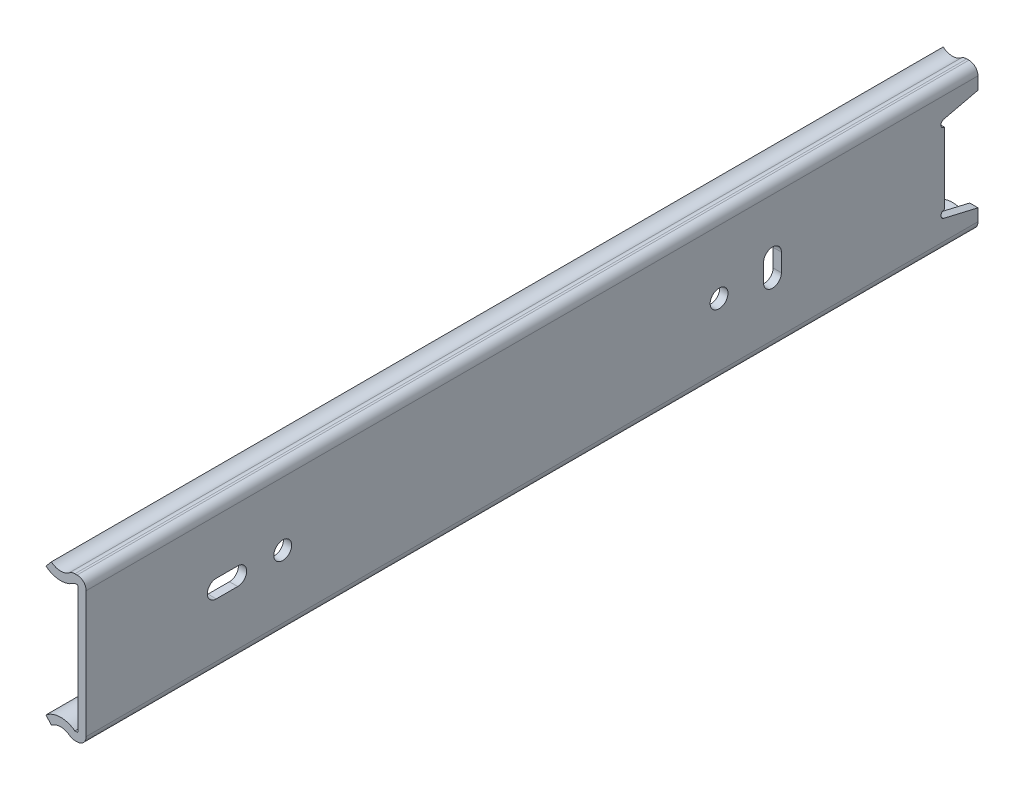
SolidWorks part; units mm, degrees
ref_plane "Front Plane" through (0, 0, 0) normal (0, 0, 1) x (1, 0, 0)
ref_plane "Top Plane" through (0, 0, 0) normal (0, 1, 0) x (1, 0, 0)
ref_plane "Right Plane" through (0, 0, 0) normal (1, 0, 0) x (0, 0, -1)
sketch "Sketch1" plane through (0, 0, 0) normal (0, 0, 1) x (1, 0, 0)
  line L0 (5.1643, -10.7505) -> (5.5418, -10.7505)
  line L1 (5.5372, 10.7505) -> (5.1643, 10.7505)
  line L2 (0.3041, 10.8422) -> (1.2082, 11.9072)
  line L3 (5.6642, 10.6235) -> (5.6642, -10.6235)
  line L4 (7.0612, -10.6235) -> (7.0612, 10.6235)
  line L5 (1.2082, -11.9072) -> (0.3041, -10.8422)
  line L22 (5.5372, 12.1475) -> (5.1643, 12.1475)
  arc A0 (5.1643, -10.7505) -> (0.3041, -10.8422) centre (2.7922, -13.8683) ccw
  arc A1 (1.2082, -11.9072) -> (4.2365, -11.8325) centre (2.7686, -13.7451) cw
  arc A2 (4.2365, -11.8325) -> (5.1643, -12.1475) centre (5.1643, -10.6235) ccw
  arc A3 (7.0612, -10.6235) -> (5.5372, -12.1475) centre (5.5372, -10.6235) cw
  arc A4 (7.0612, 10.6235) -> (5.5372, 12.1475) centre (5.5372, 10.6235) ccw
  arc A5 (5.5372, 10.7505) -> (5.6642, 10.6235) centre (5.5372, 10.6235) cw
  arc A6 (5.5418, -10.7505) -> (5.6642, -10.6235) centre (5.5371, -10.6234) ccw
  arc A7 (5.1643, 10.7505) -> (5.087, 10.7242) centre (5.1643, 10.6235) ccw
  arc A8 (5.087, 10.7242) -> (0.3041, 10.8422) centre (2.7686, 13.7451) cw
  arc A9 (1.2082, 11.9072) -> (4.2365, 11.8325) centre (2.7686, 13.7451) ccw
  arc A10 (4.2365, 11.8325) -> (5.1643, 12.1475) centre (5.1643, 10.6235) cw
  arc A11 (5.5372, -12.1475) -> (5.1643, -12.1475) centre (5.3508, -7.096) cw
extrude "Boss-Extrude1" add sketch "Sketch1" along normal blind 150 contours L3 A6 L0 A0 L5 A1 A2 A11 A3 L4 A4 L22 A10 A9 L2 A8 A7 L1 A5
sketch "Sketch2" plane through (7.0612, 0, 0) normal (1, 0, 0) x (0, 0, -1)
  line L0 (0.1195, 8.5561) -> (0.1195, -8.6225)
  line L1 (0.1195, 8.5561) -> (-5.7398, 7.188)
  line L2 (-5.5954, 5.9346) -> (-5.5954, -6.0011)
  line L3 (-5.7398, -7.2544) -> (0.1195, -8.6225)
  arc A0 (-5.7398, 7.188) -> (-5.5954, 5.9346) centre (-5.5954, 6.5696) ccw
  arc A1 (-5.5954, -6.0011) -> (-5.7398, -7.2544) centre (-5.5954, -6.6361) ccw
extrude "Cut-Extrude2" cut sketch "Sketch2" against normal through all
sketch "Sketch4" plane through (7.0612, 0, 0) normal (1, 0, 0) x (0, 0, -1)
  line L0 (-150, 0) -> (-5.5954, -0.0332) construction
  line L1 (-34.5646, 1.4741) -> (-34.5646, -1.5259) construction
  line L2 (-33.0646, 1.4741) -> (-33.0646, -1.5259)
  line L3 (-150, -10.6235) -> (-150, 10.6235) construction
  line L4 (-5.5954, 5.9346) -> (-5.5954, -6.0011) construction
  line L5 (-36.0646, 1.4741) -> (-36.0646, -1.5259)
  line L6 (-128.1242, -0.005) -> (-124.5077, -0.0059) construction
  line L7 (-128.1238, 1.495) -> (-124.5074, 1.4941)
  line L8 (-128.1245, -1.505) -> (-124.5081, -1.5059)
  arc A0 (-33.0646, 1.4741) -> (-36.0646, 1.4741) centre (-34.5646, 1.4741) ccw
  arc A1 (-36.0646, -1.5259) -> (-33.0646, -1.5259) centre (-34.5646, -1.5259) ccw
  circle A2 centre (-116.9375, -0.0076) radius 1.5
  circle A3 centre (-43.5524, -0.0245) radius 1.5
  arc A4 (-128.1238, 1.495) -> (-128.1245, -1.505) centre (-128.1242, -0.005) ccw
  arc A5 (-124.5081, -1.5059) -> (-124.5074, 1.4941) centre (-124.5077, -0.0059) ccw
  point P8 (-34.5646, -0.0259)
  point P19 (-126.316, -0.0054)
extrude "Cut-Extrude3" cut sketch "Sketch4" against normal through all
